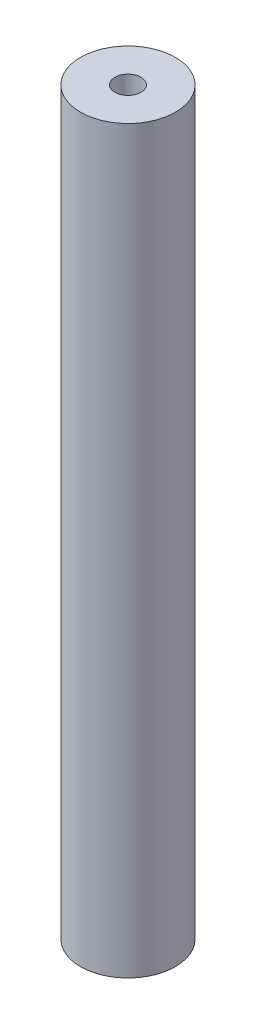
SolidWorks part; units mm, degrees
material "Aleación 6061"
ref_plane "Alzado" through (0, 0, 0) normal (0, 0, 1) x (1, 0, 0)
ref_plane "Planta" through (0, 0, 0) normal (0, 1, 0) x (1, 0, 0)
ref_plane "Vista lateral" through (0, 0, 0) normal (1, 0, 0) x (0, 0, -1)
sketch "Sk_Tubo" plane through (0, 0, 0) normal (0, 1, 0) x (1, 0, 0)
  circle A0 centre (0, -250) radius 6
  circle A1 centre (0, -250) radius 1.65
  dimension "D1" = 12
  dimension "D3" = 3.3
  dimension "D2" = 250
  dimension "D4" = 250
extrude "Tubo" add sketch "Sk_Tubo" along normal blind 93.5 from offset 46.75
